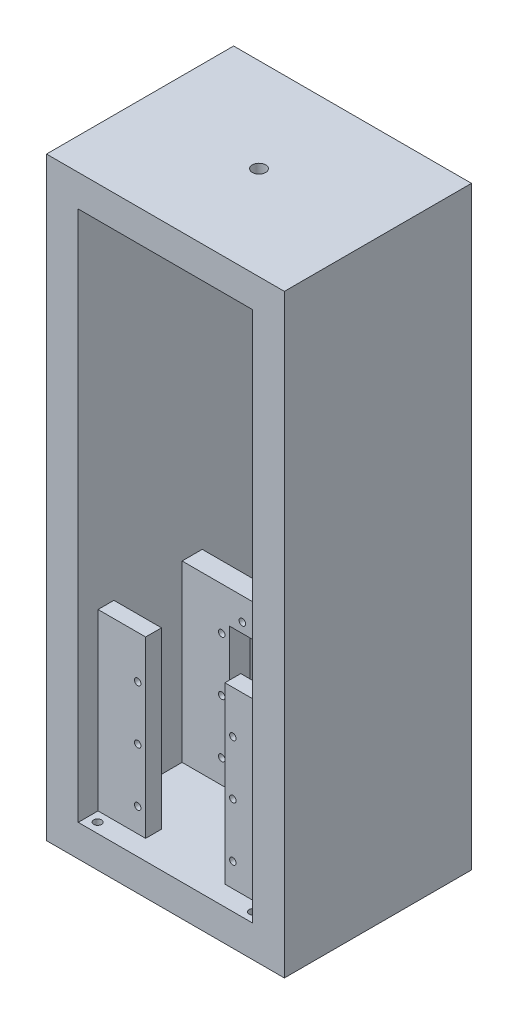
SolidWorks part; units mm, degrees
ref_plane "Front Plane" through (0, 0, 0) normal (0, 0, 1) x (1, 0, 0)
ref_plane "Top Plane" through (0, 0, 0) normal (0, 1, 0) x (1, 0, 0)
ref_plane "Right Plane" through (0, 0, 0) normal (1, 0, 0) x (0, 0, -1)
sketch "Sketch1" plane through (0, 0, 0) normal (0, 0, 1) x (1, 0, 0)
  line L1 (0, 0) -> (75, 0)
  line L2 (0, 0) -> (0, 187.5)
  line L3 (0, 187.5) -> (75, 187.5)
  line L4 (75, 0) -> (75, 187.5)
  line L5 (10, 10) -> (65, 10)
  line L6 (10, 10) -> (10, 177.5)
  line L7 (10, 177.5) -> (65, 177.5)
  line L8 (65, 10) -> (65, 177.5)
  dimension "D1" = 75
  dimension "D2" = 187.5
  dimension "D3" = 10
  dimension "D4" = 10
  dimension "D5" = 10
  dimension "D6" = 10
extrude "Boss-Extrude1" add sketch "Sketch1" against normal blind 59
ref_plane "Plane1" through (0, 0, -37.5) normal (0, 0, 1) x (1, 0, 0)
hole_wizard "Tap Drill for M5x0.8 Tap2" positions "Sketch8" profile "Sketch9" hole size "M5x0.8" standard "ANSI Metric"
sketch "Sketch8" plane through (0, 10, 0) normal (0, 1, 0) x (1, 0, 0)
  line L0 (37.5, 59) -> (37.5, 0) construction
  line L1 (10, 59) -> (65, 59) construction
  line L2 (10, 0) -> (65, 0) construction
  point P0 (37.5, 29.5)
sketch "Sketch9" plane through (37.5, 10, -29.5) normal (1, 0, 0) x (0, 0, 1)
  line L0 (0, 0) -> (0, 10)
  line L1 (0, 10) -> (2.1, 10)
  line L2 (2.1, 10) -> (2.1, 0)
  line L5 (2.1, 0) -> (0, 0)
  line L11 (0, -6.35) -> (0, 107.95) construction
  dimension "Thru Hole Dia." = 4.2
  dimension "Thru Hole Depth" = 10
hole_wizard "Tap Drill for M5x0.8 Tap3" positions "Sketch11" profile "Sketch12" hole size "M5x0.8" standard "ANSI Metric"
sketch "Sketch11" plane through (0, 187.5, 0) normal (0, 1, 0) x (1, 0, 0)
  line L0 (0, 29.5) -> (75, 29.5) construction
  line L1 (0, 59) -> (0, 0) construction
  line L2 (75, 59) -> (75, 0) construction
  point P0 (37.5, 29.5)
sketch "Sketch12" plane through (37.5, 187.5, -29.5) normal (1, 0, 0) x (0, 0, 1)
  line L0 (0, 0) -> (0, 11.2618)
  line L1 (0, 11.2618) -> (2.1, 10)
  line L2 (2.1, 10) -> (2.1, 0)
  line L5 (2.1, 0) -> (0, 0)
  line L10 (0, 11.2618) -> (-2.1, 10) construction
  line L11 (0, -6.35) -> (0, 107.95) construction
  dimension "Hole Dia." = 4.2
  dimension "Hole Depth" = 10
  dimension "Drill Angle" = 118
sketch "Sketch13" plane through (0, 10, 0) normal (0, 1, 0) x (1, 0, 0)
  line L0 (65, 59) -> (65, 0) construction
  line L1 (65, 32.75) -> (50, 32.75)
  line L2 (65, 32.75) -> (65, 39.1)
  line L3 (65, 39.1) -> (50, 39.1)
  line L4 (50, 32.75) -> (50, 39.1)
  line L5 (37.5, 59) -> (37.5, 0) construction
  line L6 (10, 59) -> (65, 59) construction
  line L7 (10, 0) -> (65, 0) construction
  line L8 (10, 39.1) -> (25, 39.1)
  line L9 (25, 32.75) -> (25, 39.1)
  line L10 (10, 32.75) -> (25, 32.75)
  line L11 (10, 32.75) -> (10, 39.1)
  line L12 (10, 11.25) -> (25, 11.25)
  line L13 (65, 6.25) -> (50, 6.25)
  line L14 (65, 6.25) -> (65, 11.25)
  line L15 (65, 11.25) -> (50, 11.25)
  line L16 (50, 6.25) -> (50, 11.25)
  line L17 (25, 6.25) -> (25, 11.25)
  line L18 (10, 6.25) -> (25, 6.25)
  line L19 (10, 6.25) -> (10, 11.25)
  dimension "D1" = 26.25
  dimension "D2" = 12.5
  dimension "D3" = 6.35
  dimension "D4" = 6.25
  dimension "D5" = 5
  dimension "D6" = 15
extrude "Boss-Extrude2" add sketch "Sketch13" along normal blind 55
sketch "Sketch14" plane through (50, 0, 0) normal (-1, 0, 0) x (0, 0, 1)
  line L0 (-32.75, 65) -> (-32.75, 10) construction
  line L1 (-39.1, 65) -> (-32.75, 65)
  line L2 (-39.1, 65) -> (-39.1, 54.7)
  line L3 (-39.1, 54.7) -> (-32.75, 54.7)
  line L4 (-32.75, 65) -> (-32.75, 54.7)
  dimension "D1" = 10.3
extrude "Boss-Extrude3" add sketch "Sketch14" along normal up to surface (25 mm away) contours L1 L4 L3 L2 up to face at (25, 37.5, -35.925)
sketch "Sketch17" plane through (0, 0, -39.1) normal (0, 0, -1) x (-1, 0, 0)
  line L0 (-37.5, 65) -> (-37.5, 10) construction
  line L1 (-65, 65) -> (-10, 65) construction
  line L2 (-10, 10) -> (-65, 10) construction
  line L3 (-22.5, 65) -> (-22.5, 10) construction
  line L5 (-25, 10) -> (-10, 10) construction
  line L6 (-29, 65) -> (-29, 10) construction
  line L8 (-65, 17.5) -> (-10, 17.5) construction
  line L9 (-65, 10) -> (-65, 177.5) construction
  line L10 (-10, 65) -> (-10, 10) construction
  line L11 (-65, 34.5) -> (-10, 34.5) construction
  line L12 (-65, 51.5) -> (-10, 51.5) construction
  line L13 (-65, 57.8) -> (-10, 57.8) construction
  line L14 (-52.5, 65) -> (-52.5, 10) construction
  line L15 (-46, 65) -> (-46, 10) construction
  dimension "D1" = 15
  dimension "D2" = 6.5
  dimension "D3" = 7.5
  dimension "D4" = 17
  dimension "D5" = 17
  dimension "D6" = 6.3
hole_wizard "Tap Drill for M2.5x0.45 Tap1" positions "Sketch18" profile "Sketch19" hole size "M2.5x0.45" standard "ANSI Metric" end condition through all
sketch "Sketch18" plane through (0, 0, -39.1) normal (0, 0, -1) x (-1, 0, 0)
  line L0 (-65, 57.8) -> (-10, 57.8) construction
  line L1 (-46, 65) -> (-46, 10) construction
  line L2 (-29, 65) -> (-29, 10) construction
  line L3 (-22.5, 65) -> (-22.5, 10) construction
  line L4 (-65, 51.5) -> (-10, 51.5) construction
  line L5 (-52.5, 65) -> (-52.5, 10) construction
  line L6 (-65, 34.5) -> (-10, 34.5) construction
  line L7 (-65, 17.5) -> (-10, 17.5) construction
  point P0 (-46, 57.8)
  point P2 (-52.5, 51.5)
  point P4 (-52.5, 34.5)
  point P6 (-52.5, 17.5)
  point P8 (-22.5, 17.5)
  point P10 (-22.5, 34.5)
  point P12 (-22.5, 51.5)
  point P14 (-29, 57.8)
sketch "Sketch19" plane through (46, 57.8, -39.1) normal (1, 0, 0) x (0, 1, 0)
  line L0 (0, 0) -> (0, 39.1)
  line L1 (0, 39.1) -> (1.025, 39.1)
  line L2 (1.025, 39.1) -> (1.025, 0)
  line L5 (1.025, 0) -> (0, 0)
  line L11 (0, -6.35) -> (0, 107.95) construction
  dimension "Thru Hole Dia." = 2.05
  dimension "Thru Hole Depth" = 39.1
hole_wizard "Tap Drill for M3x0.5 Tap1" positions "Sketch20" profile "Sketch21" hole size "M3x0.5" standard "ANSI Metric"
sketch "Sketch20" plane through (0, 10, 0) normal (0, 1, 0) x (1, 0, 0)
  line L0 (10, 3.125) -> (65, 3.125) construction
  line L1 (10, 6.25) -> (10, 0) construction
  line L2 (65, 6.25) -> (65, 0) construction
  line L4 (13, 6.25) -> (13, 0) construction
  line L5 (10, 6.25) -> (25, 6.25) construction
  line L6 (10, 0) -> (65, 0) construction
  line L8 (62, 6.25) -> (62, 0) construction
  line L9 (50, 6.25) -> (65, 6.25) construction
  line L11 (65, 53) -> (10, 53)
  line L12 (65, 59) -> (65, 39.1) construction
  line L13 (10, 59) -> (10, 39.1) construction
  line L15 (10, 59) -> (65, 59) construction
  line L16 (60, 53) -> (60, 59) construction
  line L18 (15, 53) -> (15, 59) construction
  point P0 (13, 3.125)
  point P2 (62, 3.125)
  point P37 (60, 53)
  point P39 (15, 53)
  point P59 (60, 53)
  point P60 (0, 0)
  point P61 (15, 53)
  dimension "D1" = 3
  dimension "D2" = 3
  dimension "D3" = 6
  dimension "D4" = 5
  dimension "D5" = 5
sketch "Sketch21" plane through (13, 10, -3.125) normal (1, 0, 0) x (0, 0, 1)
  line L0 (0, 0) -> (0, 10)
  line L1 (0, 10) -> (1.25, 10)
  line L2 (1.25, 10) -> (1.25, 0)
  line L5 (1.25, 0) -> (0, 0)
  line L11 (0, -6.35) -> (0, 107.95) construction
  dimension "Thru Hole Dia." = 2.5
  dimension "Thru Hole Depth" = 10
